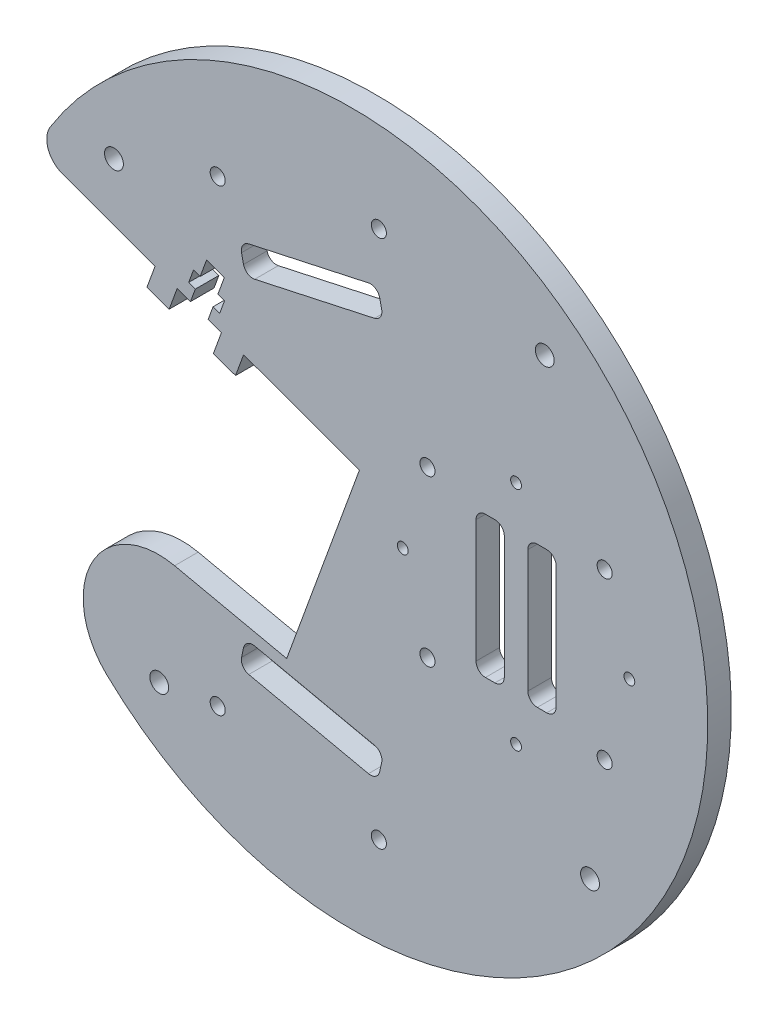
SolidWorks part; units mm, degrees
ref_plane "Plan de face" through (0, 0, 0) normal (0, 0, 1) x (1, 0, 0)
ref_plane "Plan de dessus" through (0, 0, 0) normal (0, 1, 0) x (1, 0, 0)
ref_plane "Plan de droite" through (0, 0, 0) normal (1, 0, 0) x (0, 0, -1)
sketch "Esquisse1" plane through (0, 0, 0) normal (0, 0, 1) x (1, 0, 0)
  line L0 (-41.7896, 25.5149) -> (-67.0437, 34.7187)
  line L3 (-22.9986, 18.6666) -> (1.5696, 9.7128)
  line L4 (1.5696, 9.7128) -> (-13.858, -32.6189)
  line L5 (-13.858, -32.6189) -> (-72.862, -19.7834)
  line L6 (-40.9058, -50.5145) -> (40.9058, 50.5145) construction
  line L7 (0, 0) -> (50.5145, -40.9058) construction
  line L8 (0, 0) -> (-50.5145, 40.9058) construction
  circle A0 centre (0, 0) radius 75.5 construction
  arc A1 (-67.0437, 34.7187) -> (-72.862, -19.7834) centre (0, 0) cw
  circle A2 centre (0, 0) radius 65 construction
  circle A3 centre (40.9058, 50.5145) radius 2
  circle A4 centre (-50.5145, 40.9058) radius 2
  circle A5 centre (50.5145, -40.9058) radius 2
  circle A6 centre (-40.9058, -50.5145) radius 2
  point P4 (-36.0291, 0)
  point P13 (-11.3975, 52.3938)
  point P21 (0, 0)
  point P22 (34.8192, 0)
  line B0 (-28.4976, 48.6739) -> (5.7025, 56.1137) construction
  line B1 (-14.416, 66.2693) -> (-7.4013, 34.0235) construction
  line B2 (-45.6847, 59.4672) -> (16.8527, 73.0714) construction
  line B3 (-49.5076, 53.5187) -> (-43.5558, 26.1586) construction
  line B4 (-43.5558, 26.1586) -> (28.7531, 41.8884) construction
  line B5 (22.8013, 69.2485) -> (28.7531, 41.8884) construction
  circle B6 centre (-28.4976, 48.6739) radius 1.6
  circle B7 centre (5.7025, 56.1137) radius 1.6
  circle B8 centre (5.7025, 56.1137) radius 16.6 construction
  circle B9 centre (-28.4976, 48.6739) radius 16.6 construction
  arc B10 (-45.6847, 59.4672) -> (-49.5076, 53.5187) centre (-44.6218, 54.5815) ccw construction
  arc B11 (16.8527, 73.0714) -> (22.8013, 69.2485) centre (17.9156, 68.1856) cw construction
  line B12 (-23.0151, 35.2322) -> (-23.4402, 37.1864)
  line B13 (-20.6357, 33.703) -> (4.7702, 39.2297)
  line B14 (6.2993, 41.6091) -> (5.8742, 43.5634)
  line B15 (-21.911, 39.5659) -> (3.4948, 45.0926)
  line B16 (-23.2276, 36.2093) -> (6.0868, 42.5862) construction
  arc B17 (3.4948, 45.0926) -> (5.8742, 43.5634) centre (3.9199, 43.1383) cw
  arc B18 (4.7702, 39.2297) -> (6.2993, 41.6091) centre (4.345, 41.184) ccw
  arc B19 (-20.6357, 33.703) -> (-23.0151, 35.2322) centre (-21.0608, 35.6573) cw
  arc B20 (-23.4402, 37.1864) -> (-21.911, 39.5659) centre (-21.4859, 37.6116) cw
  line B21 (5.7025, -56.1137) -> (-28.4976, -48.6739) construction
  line B22 (-14.416, -66.2693) -> (-7.4013, -34.0235) construction
  line B23 (16.8527, -73.0714) -> (-45.6847, -59.4672) construction
  line B24 (22.8013, -69.2485) -> (28.7531, -41.8884) construction
  line B25 (28.7531, -41.8884) -> (-43.5558, -26.1586) construction
  line B26 (-49.5076, -53.5187) -> (-43.5558, -26.1586) construction
  circle B27 centre (5.7025, -56.1137) radius 1.6
  circle B28 centre (-28.4976, -48.6739) radius 1.6
  circle B29 centre (-28.4976, -48.6739) radius 16.6 construction
  circle B30 centre (5.7025, -56.1137) radius 16.6 construction
  arc B31 (16.8527, -73.0714) -> (22.8013, -69.2485) centre (17.9156, -68.1856) ccw construction
  arc B32 (-45.6847, -59.4672) -> (-49.5076, -53.5187) centre (-44.6218, -54.5815) cw construction
  line B33 (6.2993, -41.6091) -> (5.8742, -43.5634)
  line B34 (4.7702, -39.2297) -> (-20.6357, -33.703)
  line B35 (-23.0151, -35.2322) -> (-23.4402, -37.1864)
  line B36 (3.4948, -45.0926) -> (-21.911, -39.5659)
  line B37 (6.0868, -42.5862) -> (-23.2276, -36.2093) construction
  arc B38 (-21.911, -39.5659) -> (-23.4402, -37.1864) centre (-21.4859, -37.6116) cw
  arc B39 (-20.6357, -33.703) -> (-23.0151, -35.2322) centre (-21.0608, -35.6573) ccw
  arc B40 (4.7702, -39.2297) -> (6.2993, -41.6091) centre (4.345, -41.184) cw
  arc B41 (5.8742, -43.5634) -> (3.4948, -45.0926) centre (3.9199, -43.1383) cw
  line B42 (53.6192, 17.5) -> (53.6192, -17.5) construction
  line B43 (67.8192, 0) -> (34.8192, 0) construction
  line B44 (67.8192, 32) -> (67.8192, -32) construction
  line B45 (62.8192, 37) -> (34.8192, 37) construction
  line B46 (34.8192, 37) -> (34.8192, -37) construction
  line B47 (62.8192, -37) -> (34.8192, -37) construction
  circle B48 centre (53.6192, 17.5) radius 1.6
  circle B49 centre (53.6192, -17.5) radius 1.6
  circle B50 centre (53.6192, -17.5) radius 16.6 construction
  circle B51 centre (53.6192, 17.5) radius 16.6 construction
  arc B52 (67.8192, 32) -> (62.8192, 37) centre (62.8192, 32) ccw construction
  arc B53 (67.8192, -32) -> (62.8192, -37) centre (62.8192, -32) cw construction
  line B54 (39.3192, 15) -> (41.3192, 15)
  line B55 (37.3192, 13) -> (37.3192, -13)
  line B56 (39.3192, -15) -> (41.3192, -15)
  line B57 (43.3192, 13) -> (43.3192, -13)
  line B58 (40.3192, 15) -> (40.3192, -15) construction
  arc B59 (43.3192, -13) -> (41.3192, -15) centre (41.3192, -13) cw
  arc B60 (37.3192, -13) -> (39.3192, -15) centre (39.3192, -13) ccw
  arc B61 (37.3192, 13) -> (39.3192, 15) centre (39.3192, 13) cw
  arc B62 (41.3192, 15) -> (43.3192, 13) centre (41.3192, 13) cw
  line B63 (16.0192, -17.5) -> (16.0192, 17.5) construction
  line B64 (1.8192, 0) -> (34.8192, 0) construction
  line B65 (1.8192, -32) -> (1.8192, 32) construction
  line B66 (6.8192, -37) -> (34.8192, -37) construction
  line B67 (34.8192, -37) -> (34.8192, 37) construction
  line B68 (6.8192, 37) -> (34.8192, 37) construction
  circle B69 centre (16.0192, -17.5) radius 1.6
  circle B70 centre (16.0192, 17.5) radius 1.6
  circle B71 centre (16.0192, 17.5) radius 16.6 construction
  circle B72 centre (16.0192, -17.5) radius 16.6 construction
  arc B73 (1.8192, -32) -> (6.8192, -37) centre (6.8192, -32) ccw construction
  arc B74 (1.8192, 32) -> (6.8192, 37) centre (6.8192, 32) cw construction
  line B75 (30.3192, -15) -> (28.3192, -15)
  line B76 (32.3192, -13) -> (32.3192, 13)
  line B77 (30.3192, 15) -> (28.3192, 15)
  line B78 (26.3192, -13) -> (26.3192, 13)
  line B79 (29.3192, -15) -> (29.3192, 15) construction
  arc B80 (26.3192, 13) -> (28.3192, 15) centre (28.3192, 13) cw
  arc B81 (32.3192, 13) -> (30.3192, 15) centre (30.3192, 13) ccw
  arc B82 (32.3192, -13) -> (30.3192, -15) centre (30.3192, -13) cw
  arc B83 (28.3192, -15) -> (26.3192, -13) centre (28.3192, -13) cw
  line B84 (-11.7846, -26.9296) -> (-71.9157, -5.015) construction
  line B85 (-71.9157, -5.015) -> (-60.2736, 26.9296) construction
  line B86 (-60.2736, 26.9296) -> (-0.1425, 5.015) construction
  line B87 (-0.1425, 5.015) -> (-11.7846, -26.9296) construction
  line B88 (-11.7846, -26.9296) -> (-60.2736, 26.9296) construction
  line B89 (-71.9157, -5.015) -> (-0.1425, 5.015) construction
  line B90 (-34.6552, 26.1078) -> (-33.628, 28.9265)
  line B91 (-28.4605, 27.0432) -> (-27.0908, 30.8014)
  line B92 (-30.849, 32.171) -> (-32.2187, 28.4128)
  line B93 (-33.628, 28.9265) -> (-32.2187, 28.4128)
  line B94 (-32.3941, 22.0907) -> (-28.5519, 32.6332) construction
  line B95 (-34.2732, 22.7756) -> (-37.0918, 23.8028)
  line B96 (-38.8039, 19.1051) -> (-43.5016, 20.8171)
  line B97 (-43.5016, 20.8171) -> (-41.7896, 25.5149)
  line B98 (-38.8039, 19.1051) -> (-37.0918, 23.8028)
  line B99 (-30.515, 21.4059) -> (-27.6963, 20.3786)
  line B100 (-27.6963, 20.3786) -> (-29.4084, 15.6809)
  line B101 (-29.4084, 15.6809) -> (-24.7107, 13.9688)
  line B102 (-24.7107, 13.9688) -> (-22.9986, 18.6666)
  line B103 (-34.2732, 22.7756) -> (-30.515, 21.4059) construction
  line B104 (-30.515, 21.4059) -> (-29.4877, 24.2245)
  line B105 (-28.4605, 27.0432) -> (-27.0512, 26.5296)
  line B106 (-28.0784, 23.7109) -> (-29.4877, 24.2245)
  line B107 (-27.0908, 30.8014) -> (-30.849, 32.171)
  line B108 (-33.2459, 25.5942) -> (-34.6552, 26.1078)
  line B109 (-27.0512, 26.5296) -> (-28.0784, 23.7109)
  line B110 (-33.2459, 25.5942) -> (-34.2732, 22.7756)
  line B111 (-28.9699, 31.4862) -> (-32.3941, 22.0907) construction
  line B112 (10.7776, 0) -> (34.8192, 24.0416) construction
  line B113 (34.8192, 24.0416) -> (58.8608, 0) construction
  line B114 (58.8608, 0) -> (34.8192, -24.0416) construction
  line B115 (34.8192, -24.0416) -> (10.7776, 0) construction
  line B116 (6.5349, 0) -> (34.8192, -28.2843) construction
  line B117 (34.8192, -28.2843) -> (63.1035, 0) construction
  line B118 (63.1035, 0) -> (34.8192, 28.2843) construction
  line B119 (34.8192, 28.2843) -> (6.5349, 0) construction
  line B120 (6.5349, 0) -> (63.1035, 0) construction
  line B121 (20.677, 14.1421) -> (48.9613, -14.1421) construction
  circle B122 centre (10.7776, 0) radius 1.15
  circle B123 centre (34.8192, 24.0416) radius 1.15
  circle B124 centre (58.8608, 0) radius 1.15
  circle B125 centre (34.8192, -24.0416) radius 1.15
  dimension "D1" = 151
  dimension "D3" = 38
  dimension "D4" = 130
  dimension "D5" = 4
  dimension "D2" = 6
  dimension "D6" = 39
sketch_block_instance "Bloc1-1"
sketch_block "Bloc1" parameters "D2"=3.2, "D6"=33.2, "D7"=5, "D11"=2, "D1"=35, "D3"=74, "D4"=33, "D5"=18.8, "D8"=25.4437, "D9"=7.7224, "D10"=25.4437
sketch_block_instance "Bloc1-3"
sketch_block_instance "Bloc1-4"
sketch_block_instance "Bloc1-5"
sketch_block_instance "Bloc2-1"
sketch_block "Bloc2" parameters "D1"=34, "D2"=64
sketch_block_instance "Insert M4 plots ep 5mm-1"
sketch_block "Insert M4 plots ep 5mm" parameters "D1"=10, "D2"=5, "D3"=5, "D4"=7, "D5"=4, "D6"=3, "D7"=3, "D8"=10
sketch_block_instance "Bloc3-1"
sketch_block "Bloc3" parameters "D4"=2.3, "D1"=34, "D2"=40, "D3"=3
extrude "Boss.-Extru.1" add sketch "Esquisse1" along normal blind 5 contours B110 B108 B90 B93 B92 B107 B91 B105 B109 B106 B104 B99 B100 B101 B102 L3 L4 L5 A1 L0 B97 B96 B98 B95 B70 B69 B49 B48 B28 B27 B7 B6 B12 B20 B15 B17 B14 B18 B13 B19 B33
fillet "Congé1" radius 16 1 edges at (-72.862, -19.7834, 2.5)
fillet "Congé2" radius 5 1 edges at (-67.0437, 34.7187, 2.5)
